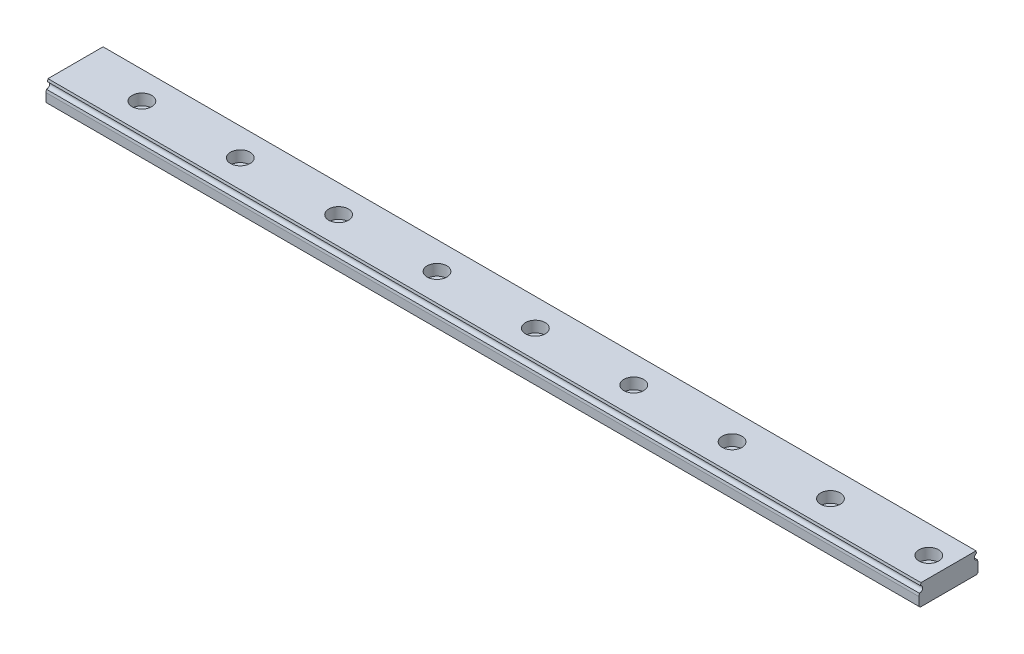
SolidWorks part; units mm, degrees
ref_plane "Plano frontal" through (0, 0, 0) normal (0, 0, 1) x (1, 0, 0)
ref_plane "Plano superior" through (0, 0, 0) normal (0, 1, 0) x (1, 0, 0)
ref_plane "Plano direito" through (0, 0, 0) normal (1, 0, 0) x (0, 0, -1)
ref_plane "Plano1" through (-15, 0, 0) normal (1, 0, 0) x (0, 0, -1)
sketch "Esboço1" plane through (-15, 0, 0) normal (1, 0, 0) x (0, 0, -1)
  line L0 (-12, 4) -> (-12, 0.5)
  line L1 (-12, 0.5) -> (-11.5, 0)
  line L2 (-11.5, 0) -> (11.5, 0)
  line L3 (11.5, 0) -> (12, 0.5)
  line L4 (12, 0.5) -> (12, 4)
  line L5 (12, 4) -> (11.8146, 5.0517)
  line L6 (11.3837, 7.4951) -> (11.2065, 8.5)
  line L7 (11.2065, 8.5) -> (-11.2065, 8.5)
  line L8 (-11.2065, 8.5) -> (-11.3837, 7.4951)
  line L9 (-11.8146, 5.0517) -> (-12, 4)
  arc A0 (11.8146, 5.0517) -> (11.3837, 7.4951) centre (11.75, 6.3) cw
  arc A1 (-11.3837, 7.4951) -> (-11.8146, 5.0517) centre (-11.75, 6.3) cw
extrude "Ressalto-extrusão1" add sketch "Esboço1" along normal blind 263 and the other way blind 92
ref_plane "Plano2" through (0, 0, 0) normal (0, 0, 1) x (1, 0, 0)
sketch "Esboço2" plane through (0, 0, 0) normal (0, 0, 1) x (1, 0, 0)
  line L0 (0, 8.5) -> (4, 8.5)
  line L1 (4, 8.5) -> (4, 4)
  line L2 (4, 4) -> (2.25, 4)
  line L3 (2.25, 4) -> (2.25, 0)
  line L4 (2.25, 0) -> (0, 0)
  line L5 (0, 0) -> (0, 8.5)
  line L6 (0, 0) -> (0, 8.5) construction
ref_plane "Plano3" through (0, 0, 0) normal (0, 0, 1) x (1, 0, 0)
sketch "Esboço3" plane through (0, 0, 0) normal (0, 0, 1) x (1, 0, 0)
  line L0 (40, 8.5) -> (44, 8.5)
  line L1 (44, 8.5) -> (44, 4)
  line L2 (44, 4) -> (42.25, 4)
  line L3 (42.25, 4) -> (42.25, 0)
  line L4 (42.25, 0) -> (40, 0)
  line L5 (40, 0) -> (40, 8.5)
  line L6 (40, 0) -> (40, 8.5) construction
revolve "Corte-Revolução2" cut sketch "Esboço3" angle 360 about L6
pattern_linear "LPattern1" count 6 spacing 40 along (1, 0, 0) count 4 spacing 40 along (-1, 0, 0) of "Corte-Revolução2"
